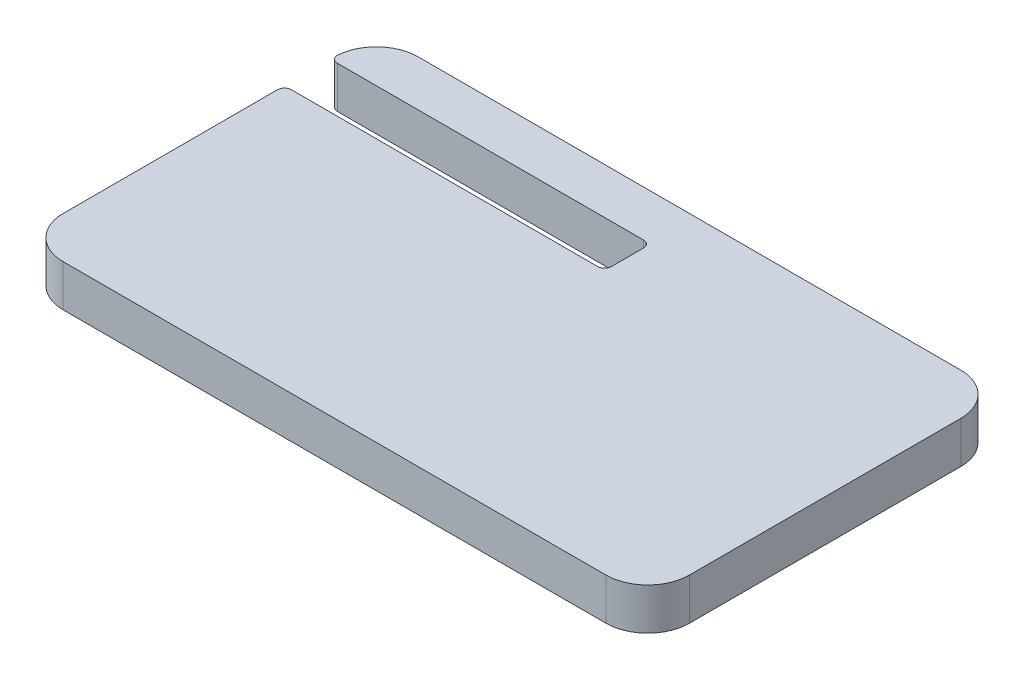
SolidWorks part; units mm, degrees
ref_plane "Alzado" through (0, 0, 0) normal (0, 0, 1) x (1, 0, 0)
ref_plane "Planta" through (0, 0, 0) normal (0, 1, 0) x (1, 0, 0)
ref_plane "Vista lateral" through (0, 0, 0) normal (1, 0, 0) x (0, 0, -1)
sketch "Croquis1" plane through (0, 0, 0) normal (0, 1, 0) x (1, 0, 0)
  line L5 (-22.5, 9.9298) -> (22.5, 9.9298)
  line L6 (-22.5, 9.9298) -> (-22.5, -15.5702)
  line L7 (-22.5, -15.5702) -> (22.5, -15.5702)
  line L8 (22.5, 9.9298) -> (22.5, -15.5702)
  dimension "D1" = 9.9298
  dimension "D2" = 22.5
  dimension "D3" = 25.5
  dimension "D4" = 45
extrude "Saliente-Extruir1" add sketch "Croquis1" along normal blind 3
sketch "Croquis2" plane through (0, 3, 0) normal (0, 1, 0) x (1, 0, 0)
  line L0 (-22.5, 9.9298) -> (-22.5, -15.5702) construction
  line L1 (-22.5, 6.6298) -> (0.5, 6.6298)
  line L2 (-22.5, 6.6298) -> (-22.5, 3.3298)
  line L3 (-22.5, 3.3298) -> (0.5, 3.3298)
  line L4 (0.5, 6.6298) -> (0.5, 3.3298)
  line L6 (22.5, 9.9298) -> (-22.5, 9.9298) construction
  dimension "D1" = 23
  dimension "D2" = 3.3
  dimension "D3" = 3.3
extrude "Cortar-Extruir1" cut sketch "Croquis2" against normal up to surface (3 mm away) up to face at (0, 0, 2.8202)
fillet "Redondeo1" radius 3 4 edges at (-22.5, 1.5, 15.5702) (-22.5, 1.5, -9.9298) (22.5, 1.5, 15.5702) (22.5, 1.5, -9.9298)
fillet "Redondeo4" radius 0.5 4 edges at (-22.5, 1.5, -3.3298) (0.5, 1.5, -3.3298) (0.5, 1.5, -6.6298) (-22.5, 1.5, -6.6298)
